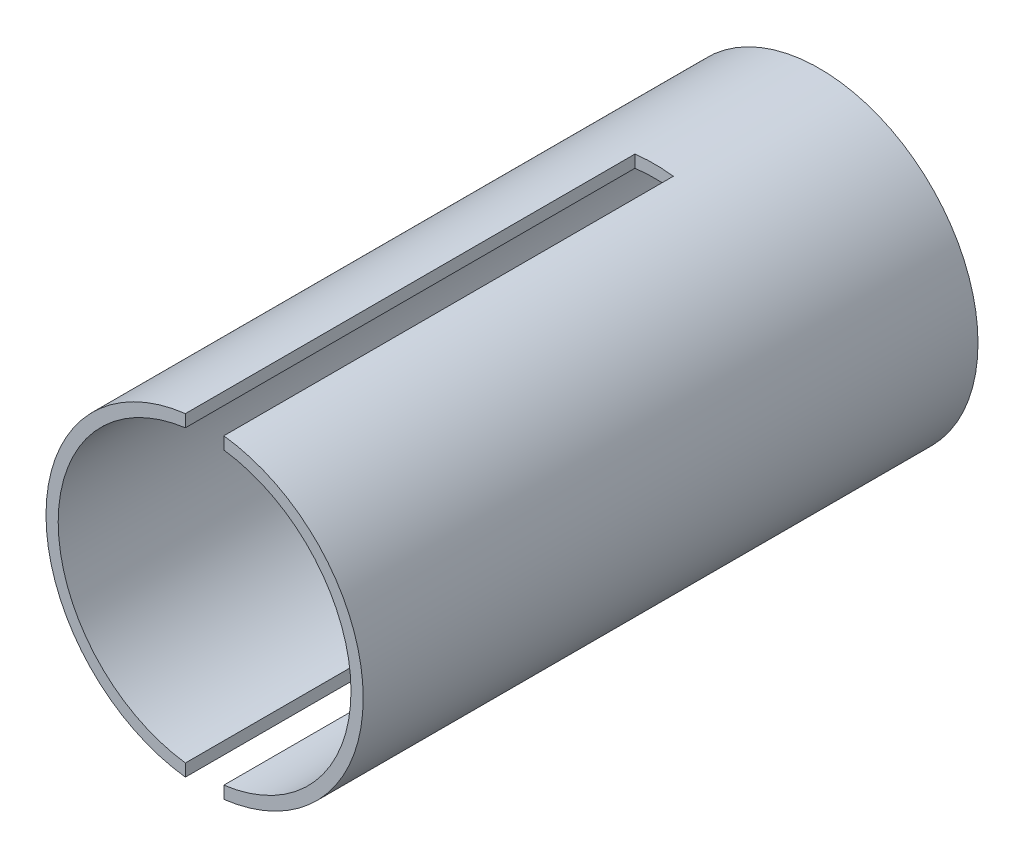
SolidWorks part; units mm, degrees
ref_plane "Front Plane" through (0, 0, 0) normal (0, 0, 1) x (1, 0, 0)
ref_plane "Top Plane" through (0, 0, 0) normal (0, 1, 0) x (1, 0, 0)
ref_plane "Right Plane" through (0, 0, 0) normal (1, 0, 0) x (0, 0, -1)
sketch "Sketch1" plane through (0, 0, 0) normal (0, 0, 1) x (1, 0, 0)
  circle A0 centre (0, 0) radius 38.1
  circle A1 centre (0, 0) radius 41.275
  dimension "D1" = 76.2
  dimension "D2" = 82.55
extrude "Boss-Extrude1" add sketch "Sketch1" along normal blind 160
sketch "Sketch2" plane through (0, 0, 0) normal (0, 1, 0) x (1, 0, 0)
  line L0 (-41.275, -160) -> (41.275, -160) construction
  line L1 (5, -220) -> (-5, -220) construction
  line L2 (5, -220) -> (5, -100) construction
  line L3 (5, -100) -> (-5, -100) construction
  line L4 (-5, -220) -> (-5, -100) construction
  line L5 (5, -220) -> (-5, -100) construction
  line L6 (5, -100) -> (-5, -220) construction
  line L7 (-5, -160) -> (5, -160)
  line L8 (5, -160) -> (5, -100)
  line L9 (-5, -100) -> (-5, -160)
  line L10 (-5, -100) -> (5, -100)
  point P0 (0, -160)
  dimension "D1" = 60
  dimension "D2" = 10
extrude "Cut-Extrude1" cut sketch "Sketch2" against normal blind 50
sketch "Sketch3" plane through (0, 0, 0) normal (0, 1, 0) x (1, 0, 0)
  line L0 (-41.275, -160) -> (41.275, -160) construction
  line L1 (-5, -277) -> (5, -277)
  line L2 (-5, -277) -> (-5, -43) construction
  line L3 (-5, -43) -> (5, -43)
  line L4 (5, -277) -> (5, -43) construction
  line L5 (-5, -277) -> (5, -43) construction
  line L6 (-5, -43) -> (5, -277) construction
  line L7 (-5, -160) -> (5, -160)
  line L8 (5, -160) -> (5, -43)
  line L9 (-5, -43) -> (-5, -160)
  point P0 (0, -160)
  dimension "D1" = 117
  dimension "D2" = 10
extrude "Cut-Extrude2" cut sketch "Sketch3" along normal blind 50 contours L3 L9 L7 L8
